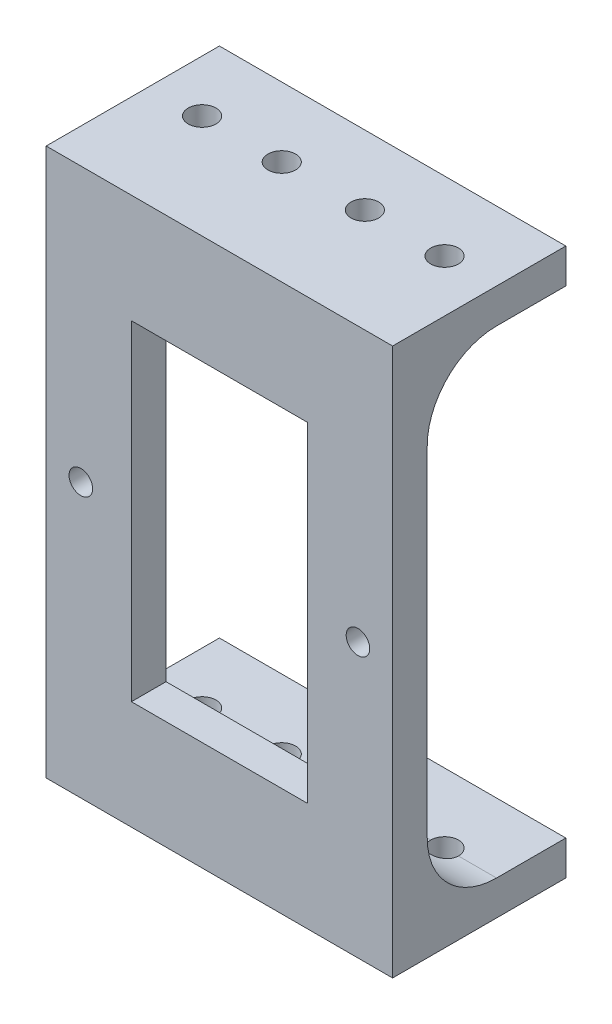
SolidWorks part; units mm, degrees
ref_plane "Front Plane" through (0, 0, 0) normal (0, 0, 1) x (1, 0, 0)
ref_plane "Top Plane" through (0, 0, 0) normal (0, 1, 0) x (1, 0, 0)
ref_plane "Right Plane" through (0, 0, 0) normal (1, 0, 0) x (0, 0, -1)
sketch "Sketch1" plane through (0, 0, 0) normal (0, 0, 1) x (1, 0, 0)
  line L0 (-25, 0) -> (25, 0) construction
  line L1 (25, -39.5) -> (-25, -39.5)
  line L2 (25, -39.5) -> (25, 39.5)
  line L3 (25, 39.5) -> (-25, 39.5)
  line L4 (-25, -39.5) -> (-25, 39.5)
  line L5 (25, -39.5) -> (-25, 39.5) construction
  line L6 (25, 39.5) -> (-25, -39.5) construction
  line L7 (12.7, -23.8125) -> (-12.7, -23.8125)
  line L8 (12.7, -23.8125) -> (12.7, 23.8125)
  line L9 (12.7, 23.8125) -> (-12.7, 23.8125)
  line L10 (-12.7, -23.8125) -> (-12.7, 23.8125)
  line L11 (12.7, -23.8125) -> (-12.7, 23.8125) construction
  line L12 (12.7, 23.8125) -> (-12.7, -23.8125) construction
  circle A0 centre (-20, 0) radius 1.7
  circle A1 centre (20, 0) radius 1.7
  point P0 (0, 0)
  point P6 (0, 0)
  dimension "D5" = 5
  dimension "D6" = 3.4
  dimension "D7" = 5
  dimension "D8" = 3.4
  dimension "D1" = 79
  dimension "D2" = 50
  dimension "D3" = 47.625
  dimension "D4" = 25.4
extrude "Boss-Extrude1" add sketch "Sketch1" along normal blind 5
sketch "Sketch2" plane through (-25, 0, 0) normal (-1, 0, 0) x (0, 0, 1)
  line L1 (-20, 34.5) -> (0, 34.5)
  line L2 (-20, 34.5) -> (-20, 39.5)
  line L3 (-20, 39.5) -> (0, 39.5)
  line L4 (0, 34.5) -> (0, 39.5)
  line L5 (0, -39.5) -> (-20, -39.5)
  line L6 (0, -39.5) -> (0, -34.5)
  line L7 (0, -34.5) -> (-20, -34.5)
  line L8 (-20, -39.5) -> (-20, -34.5)
  dimension "D1" = 20
  dimension "D2" = 5
  dimension "D3" = 5
  dimension "D4" = 20
extrude "Boss-Extrude2" add sketch "Sketch2" against normal up to surface (50 mm away) up to face at (25, 0, 2.5)
fillet "Fillet1" radius 10 2 edges at (0, -34.5, 0) (0, 34.5, 0)
sketch "Sketch3" plane through (0, 39.5, 0) normal (0, 1, 0) x (1, 0, 0)
  line L0 (-25, 10) -> (25, 10) construction
  line L1 (-25, -5) -> (-25, 20) construction
  line L2 (25, 20) -> (-25, 20) construction
  line L3 (25, -5) -> (25, 20) construction
  circle A0 centre (-17.5, 10) radius 2
  circle A1 centre (-6, 10) radius 2
  circle A2 centre (6, 10) radius 2
  circle A3 centre (17.5, 10) radius 2
  point P14 (0, 0)
  dimension "D2" = 4
  dimension "D3" = 7.5
  dimension "D4" = 11.5
  dimension "D5" = 11.5
  dimension "D6" = 7.5
  dimension "D1" = 10
extrude "Cut-Extrude1" cut sketch "Sketch3" against normal through all both and the other way through all
